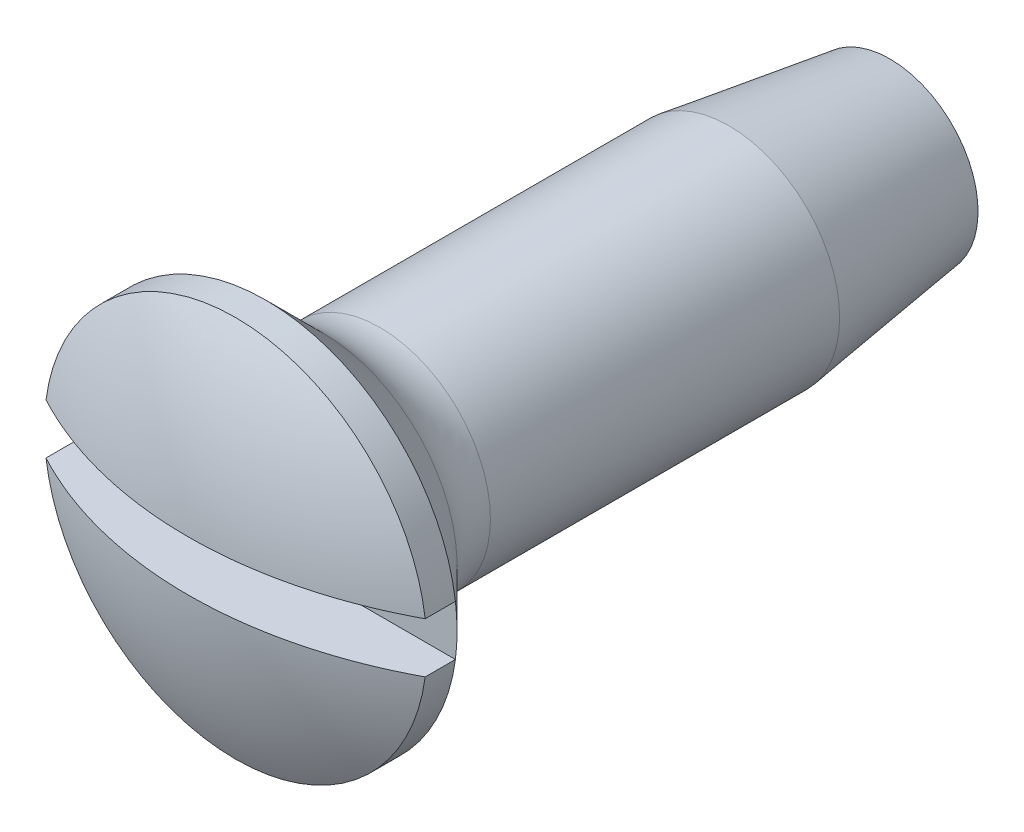
SolidWorks part; units mm, degrees
material "普通碳钢"
ref_plane "前视" through (0, 0, 0) normal (0, 0, 1) x (1, 0, 0)
ref_plane "上视" through (0, 0, 0) normal (0, 1, 0) x (1, 0, 0)
ref_plane "右视" through (0, 0, 0) normal (1, 0, 0) x (0, 0, -1)
sketch "尺寸草图" plane through (0, 0, 0) normal (1, 0, 0) x (0, 0, -1)
  line L0 (-6.5, 4) -> (-6.5, 0)
  line L1 (-6.5, 0) -> (0, 0)
  line L2 (0, 0) -> (0, 2.2)
  point P4 (0, 0.8)
  point P6 (-6, 0)
  point P7 (-5.4, 0)
  point P8 (-4.6, 0)
  point P9 (-4.1, 0)
  point P10 (-6.5, 0.8)
  point P11 (-0.8, 0)
  point P12 (-6.5, 3.8)
  point P13 (-1.6, 0)
  dimension "l" = 6.5
  dimension "rf" = 4
  dimension "d" = 2.2
  dimension "dk" = 3.8
  dimension "t" = 0.8
  dimension "f" = 0.5
  dimension "K" = 1.1
  dimension "a" = 0.8
  dimension "P" = 0.8
  dimension "n" = 0.5
  dimension "r" = 0.8
  dimension "yf" = 1.6
sketch "草图1" plane through (0, 0, 0) normal (1, 0, 0) x (0, 0, -1)
  line L0 (0.4555, 0) -> (-7.8887, 0) construction
  line L1 (0, 0) -> (-6.9801, 0)
  line L2 (-1.6, 1.1) -> (0, 0.8751)
  line L3 (-6.5, 1.9) -> (-6.2, 1.9)
  line L4 (-6.2, 1.9) -> (-5.4, 1.1)
  line L5 (-5.4, 1.1) -> (-1.6, 1.1)
  line L6 (0, 0.8751) -> (0, 0)
  arc A0 (-6.9801, 0) -> (-6.5, 1.9) centre (-2.9801, 0) cw
  point P9 (0, 1.1)
  dimension "D7" = 4
  dimension "D1" = 6.5
  dimension "D2" = 3.8
  dimension "D3" = 2.2
  dimension "D4" = 45
  dimension "D5" = 1.6
  dimension "D6" = 1.1
  dimension "D8" = 8
revolve "基体-旋转" add sketch "草图1"
cosmetic thread "装饰螺纹线1"
fillet "圆角1" radius 0.8 1 edges at (0, 1.1, 5.4)
sketch "草图2" plane through (0, 0, 0) normal (1, 0, 0) x (0, 0, -1)
  line L1 (-7, 0.25) -> (-6.2, 0.25)
  line L2 (-7, 0.25) -> (-7, -0.25)
  line L3 (-7, -0.25) -> (-6.2, -0.25)
  line L4 (-6.2, 0.25) -> (-6.2, -0.25)
  point P4 (-7, 0)
  dimension "D1" = 7
  dimension "D2" = 0.5
  dimension "D3" = 0.8
extrude "切除-拉伸1" cut sketch "草图2" against normal mid plane 100
sketch "草图3" plane through (0, 0, 0) normal (1, 0, 0) x (0, 0, -1)
  line L0 (-4.6, 1.1) -> (-3.8, 1.1)
  line L1 (-3.8, 1.1) -> (-3.9865, 0.7)
  line L2 (-3.9865, 0.7) -> (-4.4135, 0.7)
  line L3 (-4.4135, 0.7) -> (-4.6, 1.1)
  line L4 (-6.9668, 0) -> (0.1037, 0) construction
  line L5 (0.4555, 0) -> (-7.8887, 0) construction
  line L6 (-5.4, 1.1) -> (-5.4, -1.1) construction
  dimension "D1" = 0.8
  dimension "D2" = 65
  dimension "D3" = 0.4
  dimension "D4" = 2.2
  dimension "D5" = 0.8
revolve "切除-旋转1" [suppressed] cut sketch "草图3" angle 360 about L4
pattern_linear "阵列(线性)1" [suppressed] count 5 spacing 0.8889
ref_plane "Bface1" through (0, 0, 6.2) normal (0, 0, -1) x (-0.0916, 0.9958, 0)
